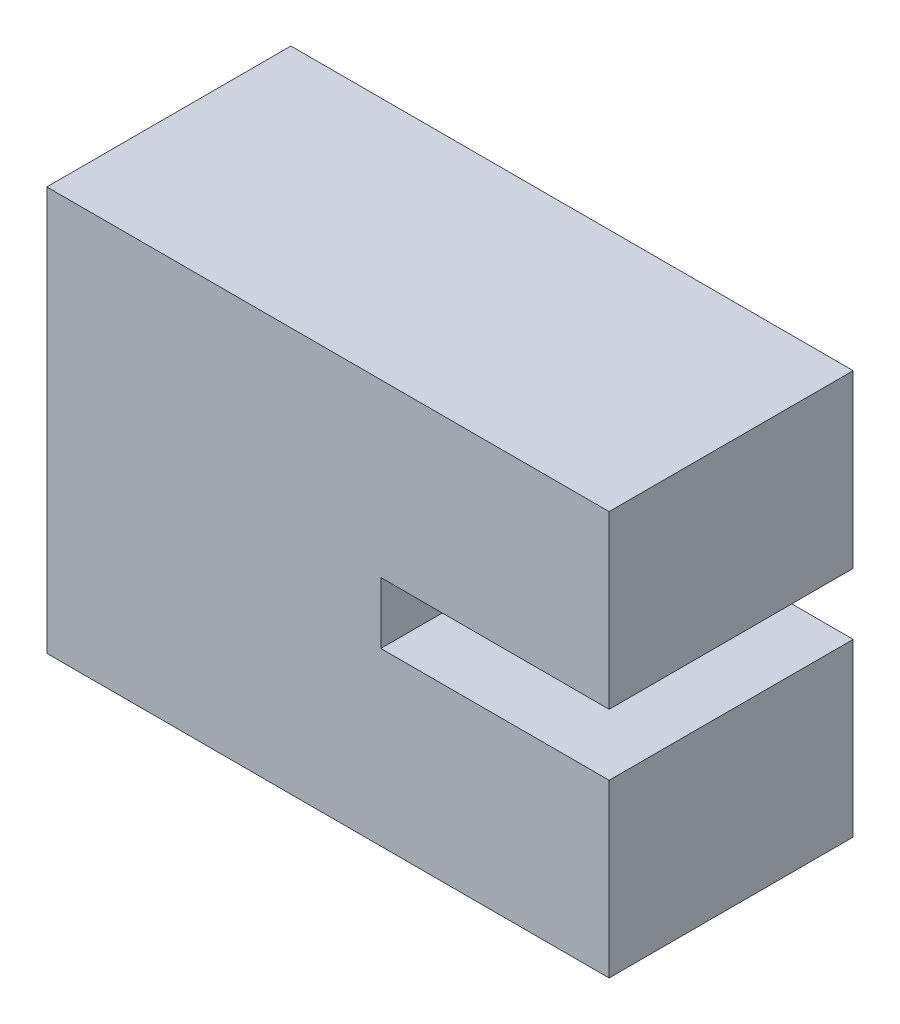
SolidWorks part; units mm, degrees
ref_plane "Front Plane" through (0, 0, 0) normal (0, 0, 1) x (1, 0, 0)
ref_plane "Top Plane" through (0, 0, 0) normal (0, 1, 0) x (1, 0, 0)
ref_plane "Right Plane" through (0, 0, 0) normal (1, 0, 0) x (0, 0, -1)
sketch "Sketch1" plane through (0, 0, 0) normal (0, 0, 1) x (1, 0, 0)
  line L0 (0, 0) -> (0, 14.1537)
  line L1 (0, 14.1537) -> (19.7046, 14.1537)
  line L2 (19.7046, 14.1537) -> (19.7046, 8.1537)
  line L3 (19.7046, 8.1537) -> (11.7046, 8.1537)
  line L4 (11.7046, 8.1537) -> (11.7046, 6)
  line L5 (11.7046, 6) -> (19.7046, 6)
  line L6 (19.7046, 6) -> (19.7046, 0)
  line L7 (19.7046, 0) -> (0, 0)
  dimension "D1" = 8
  dimension "D2" = 2.1537
  dimension "D3" = 6
extrude "Boss-Extrude1" add sketch "Sketch1" along normal blind 8.553
